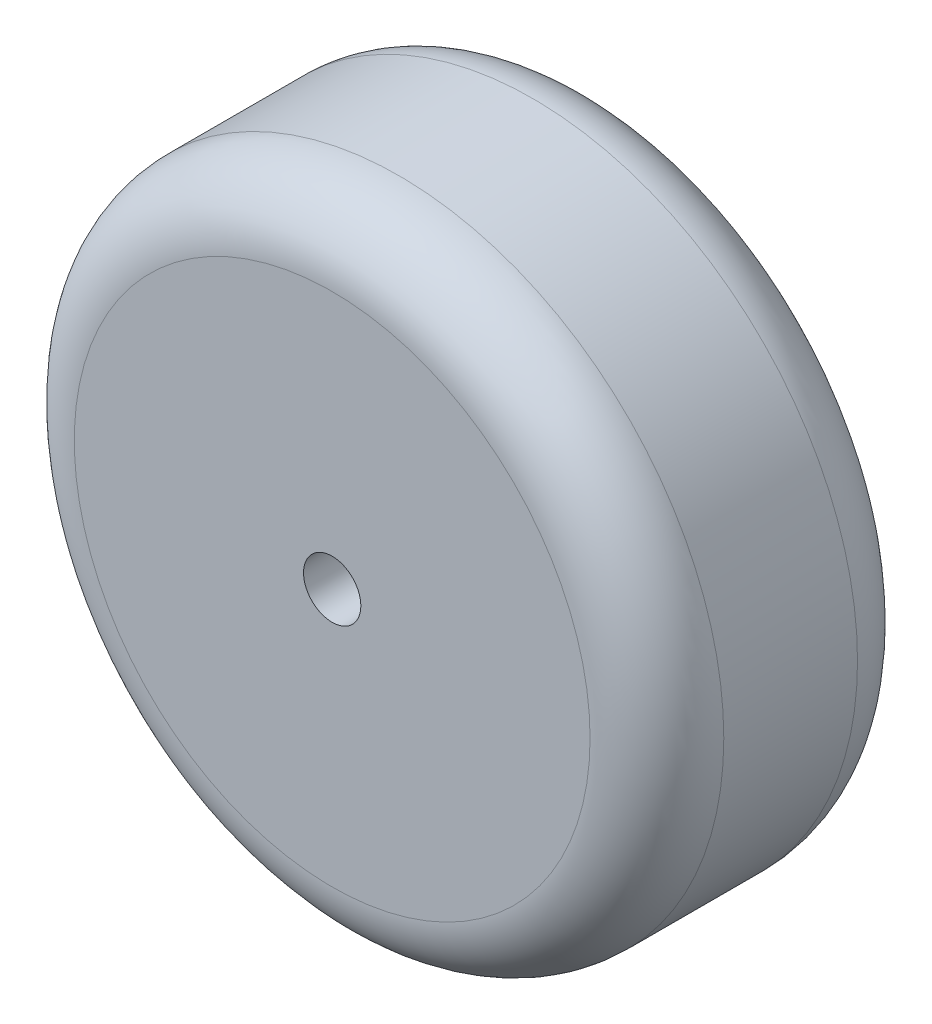
SolidWorks part; units mm, degrees
ref_plane "Plano frontal" through (0, 0, 0) normal (0, 0, 1) x (1, 0, 0)
ref_plane "Plano superior" through (0, 0, 0) normal (0, 1, 0) x (1, 0, 0)
ref_plane "Plano direito" through (0, 0, 0) normal (1, 0, 0) x (0, 0, -1)
sketch "Esboço1" plane through (0, 0, 0) normal (0, 0, 1) x (1, 0, 0)
  circle A0 centre (-5.7956, 6.5324) radius 34
  circle A1 centre (-5.7956, 6.5324) radius 3
  dimension "D1" = 6
  dimension "D2" = 68
extrude "Ressalto-extrusão3" add sketch "Esboço1" along normal blind 28 contours A1 | A0
fillet "Filete2" radius 7 2 edges at (28.2044, 6.5324, 28) (28.2044, 6.5324, 0)
